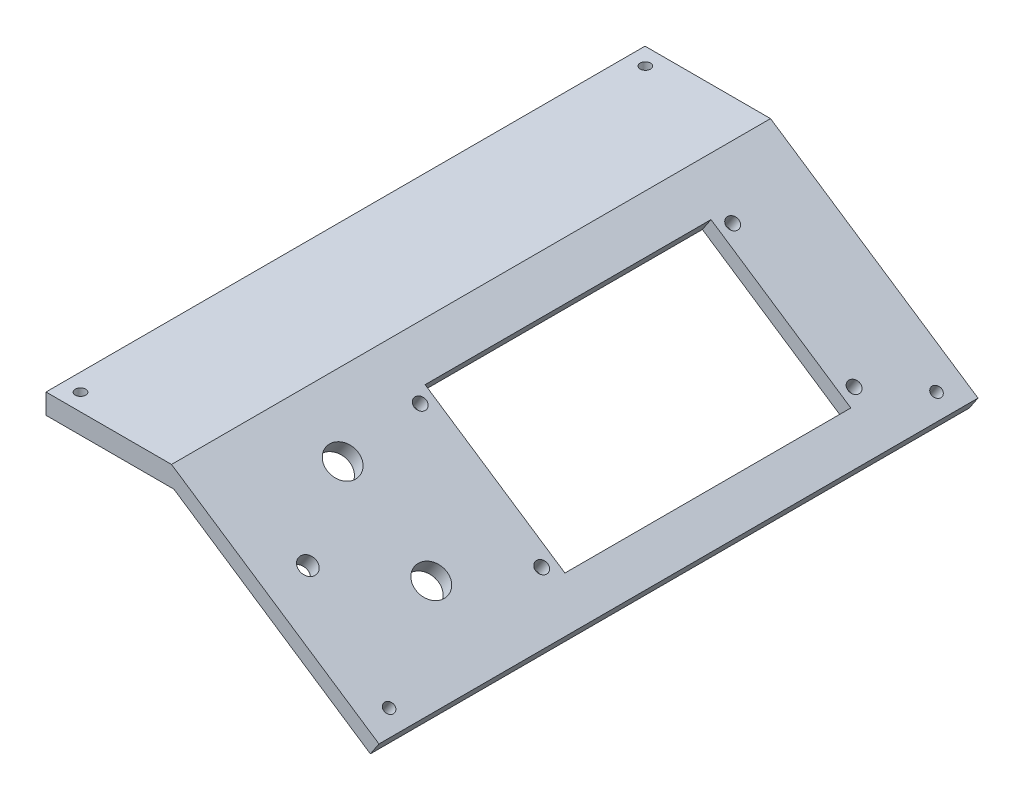
SolidWorks part; units mm, degrees
ref_plane "Plano frontal" through (0, 0, 0) normal (0, 0, 1) x (1, 0, 0)
ref_plane "Plano superior" through (0, 0, 0) normal (0, 1, 0) x (1, 0, 0)
ref_plane "Plano direito" through (0, 0, 0) normal (1, 0, 0) x (0, 0, -1)
sketch "Esboço1" plane through (0, 0, 0) normal (0, 0, 1) x (1, 0, 0)
  line L0 (0, 0) -> (36, 0)
  line L7 (0, 0) -> (0, -5.8)
  line L8 (0, -5.8) -> (36.6776, -5.8)
  line L14 (95.5008, -39.6672) -> (36, 0)
  line L15 (93.5316, -43.7026) -> (33.5316, -3.7026) construction
  line L16 (93.0324, -43.3698) -> (36.6776, -5.8)
  line L18 (95.5008, -39.6672) -> (93.0324, -43.3698)
  line L20 (96, -40) -> (36, 0) construction
  dimension "D2" = 36
  dimension "D3" = 5.8
extrude "Ressalto-extrusão1" add sketch "Esboço1" along normal blind 171.8
sketch "Esboço2" plane through (11.0769, 16.6154, 0) normal (0.5547, 0.8321, 0) x (0.8321, -0.5547, 0)
  line L0 (41.8833, -27) -> (41.8833, -109)
  line L3 (90.0833, -27) -> (90.0833, -109)
  line L6 (41.8833, -109) -> (90.0833, -109)
  line L7 (41.8833, -27) -> (90.0833, -27)
  circle A0 centre (44.7793, -112.8) radius 1.75
  circle A1 centre (86.6393, -112.8) radius 1.75
  circle A2 centre (44.7793, -23.2) radius 1.75
  circle A3 centre (86.6393, -23.2) radius 1.75
  circle A4 centre (77.6648, -137) radius 4.5
  circle A5 centre (47.1182, -137) radius 4.5
  circle A6 centre (62.1648, -159.5) radius 2.5
  circle A7 centre (96.0648, -164.4) radius 1.5
  circle A8 centre (96.0648, -7.4) radius 1.5
extrude "Corte-extrusão1" cut sketch "Esboço2" against normal blind 91.8
sketch "Esboço3" plane through (0, 0, 0) normal (0, 1, 0) x (1, 0, 0)
  circle A0 centre (5, -166.9) radius 1.5
  circle A1 centre (5, -4.9) radius 1.5
extrude "Corte-extrusão2" cut sketch "Esboço3" against normal blind 91.8
